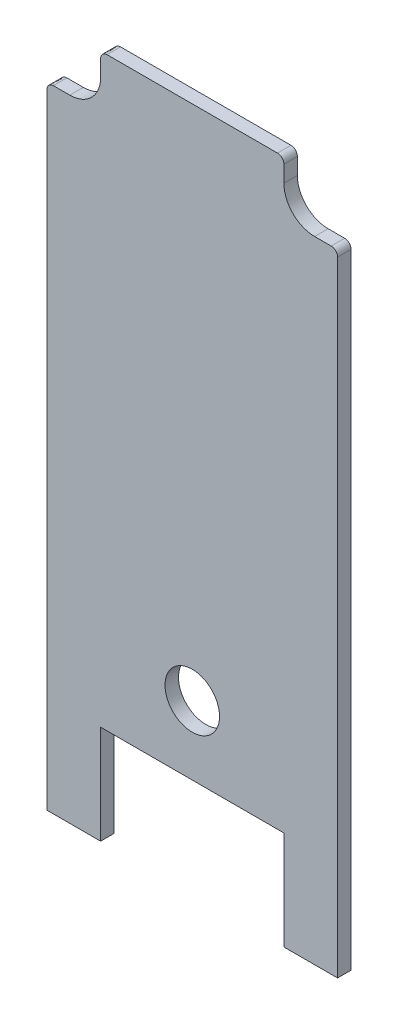
SolidWorks part; units mm, degrees
ref_plane "Front Plane" through (0, 0, 0) normal (0, 0, 1) x (1, 0, 0)
ref_plane "Top Plane" through (0, 0, 0) normal (0, 1, 0) x (1, 0, 0)
ref_plane "Right Plane" through (0, 0, 0) normal (1, 0, 0) x (0, 0, -1)
sketch3d "3DSketch1" plane through (0, 0, 0) normal (0, 0, 1) x (1, 0, 0)
  dimension "D1" = 5
sketch "Sketch2" plane through (0, 0, 5) normal (0, 0, 1) x (1, 0, 0)
  line L0 (-18.9245, -40.3) -> (-18.9245, 40.3)
  line L1 (13.25, -45.9745) -> (-13.25, -45.9745)
  line L2 (-13.25, 45.9745) -> (13.25, 45.9745)
  line L3 (18.9245, 40.3) -> (18.9245, -40.3)
  line L4 (-16.1749, 37.9745) -> (-14.25, 37.9745)
  line L5 (10.9245, 43.2249) -> (10.9245, 41.3)
  line L6 (17.1745, 36.9749) -> (17.1745, -37.0249)
  line L7 (14.25, 37.9745) -> (16.1749, 37.9745)
  line L8 (-9.9249, 44.2245) -> (9.9249, 44.2245)
  line L9 (-10.9245, 41.3) -> (-10.9245, 43.2249)
  line L10 (-17.1745, -36.9249) -> (-17.1745, 36.9749)
  line L11 (-14.25, -37.9245) -> (-16.1749, -37.9245)
  line L12 (-10.8745, -43.2249) -> (-10.8745, -41.3)
  line L13 (9.9749, -44.2245) -> (-9.8749, -44.2245)
  line L14 (10.9745, -41.3) -> (10.9745, -43.2249)
  line L15 (16.1749, -38.0245) -> (14.25, -38.0245)
  line L16 (16.1749, -38.0245) -> (14.25, -38.0245) construction
  line L17 (10.9745, -41.3) -> (10.9745, -43.2249) construction
  line L18 (9.9749, -44.2245) -> (-9.8749, -44.2245) construction
  line L19 (-10.8745, -43.2249) -> (-10.8745, -41.3) construction
  line L20 (-14.25, -37.9245) -> (-16.1749, -37.9245) construction
  line L21 (-17.1745, -36.9249) -> (-17.1745, 36.9749) construction
  line L22 (-10.9245, 41.3) -> (-10.9245, 43.2249) construction
  line L23 (-9.9249, 44.2245) -> (9.9249, 44.2245) construction
  line L24 (14.25, 37.9745) -> (16.1749, 37.9745) construction
  line L25 (17.1745, 36.9749) -> (17.1745, -37.0249) construction
  line L26 (10.9245, 43.2249) -> (10.9245, 41.3) construction
  line L27 (-16.1749, 37.9745) -> (-14.25, 37.9745) construction
  line L28 (18.9245, 40.3) -> (18.9245, -40.3) construction
  line L29 (-13.25, 45.9745) -> (13.25, 45.9745) construction
  line L30 (13.25, -45.9745) -> (-13.25, -45.9745) construction
  line L31 (-18.9245, -40.3) -> (-18.9245, 40.3) construction
  line L32 (-16.9205, -24.2245) -> (-16.9205, 36.9749)
  line L33 (-16.1749, 37.7205) -> (-14.25, 37.7205)
  line L34 (-10.6705, 41.3) -> (-10.6705, 43.2249)
  line L35 (-9.9249, 43.9705) -> (9.9249, 43.9705)
  line L36 (10.6705, 43.2249) -> (10.6705, 41.3)
  line L37 (14.25, 37.7205) -> (16.1749, 37.7205)
  line L38 (16.9205, 36.9749) -> (16.9205, -35.7245)
  line L44 (-10.6705, -24.2245) -> (10.6705, -24.2245)
  line L45 (-16.9205, -36.8196) -> (-16.9205, 36.9749) construction
  line L46 (16.9205, 36.9749) -> (16.9205, -36.9196) construction
  line L47 (17.1745, -37.0249) -> (16.1749, -38.0245) construction
  line L48 (16.9205, -36.9196) -> (16.0696, -37.7705) construction
  line L49 (10.9745, -43.2249) -> (9.9749, -44.2245) construction
  line L50 (10.7205, -43.1196) -> (9.8696, -43.9705) construction
  line L51 (-9.8749, -44.2245) -> (-10.8745, -43.2249) construction
  line L52 (-9.7696, -43.9705) -> (-10.6205, -43.1196) construction
  line L53 (-16.1749, -37.9245) -> (-17.1745, -36.9249) construction
  line L54 (-16.0696, -37.6705) -> (-16.9205, -36.8196) construction
  line L55 (0, -45.9745) -> (0, 45.9745) construction
  line L56 (-16.9205, -24.2245) -> (-10.6705, -24.2245)
  line L57 (-16.9205, -24.2245) -> (-16.9205, -35.7245)
  line L58 (-16.9205, -35.7245) -> (-10.6705, -35.7245)
  line L59 (-10.6705, -24.2245) -> (-10.6705, -35.7245)
  line L60 (16.0696, -37.7705) -> (14.25, -37.7705) construction
  line L61 (10.7205, -41.3) -> (10.7205, -43.1196) construction
  line L62 (9.8696, -43.9705) -> (-9.7696, -43.9705) construction
  line L63 (-10.6205, -43.1196) -> (-10.6205, -41.3) construction
  line L64 (-14.25, -37.6705) -> (-16.0696, -37.6705) construction
  line L65 (10.6705, -24.2245) -> (10.6705, -35.7245)
  line L66 (16.9205, -35.7245) -> (10.6705, -35.7245)
  arc A0 (-18.9245, -40.3) -> (-13.25, -45.9745) centre (-13.25, -40.3) ccw
  arc A1 (-13.25, 45.9745) -> (-18.9245, 40.3) centre (-13.25, 40.3) ccw
  arc A2 (18.9245, 40.3) -> (13.25, 45.9745) centre (13.25, 40.3) ccw
  arc A3 (13.25, -45.9745) -> (18.9245, -40.3) centre (13.25, -40.3) ccw
  arc A4 (-14.25, 37.9745) -> (-10.9245, 41.3) centre (-14.25, 41.3) ccw
  arc A5 (10.9245, 41.3) -> (14.25, 37.9745) centre (14.25, 41.3) ccw
  circle A6 centre (14.25, -41.3) radius 1.321
  circle A7 centre (-14.25, 41.3) radius 1.321
  circle A8 centre (-14.25, -41.3) radius 1.321
  circle A9 centre (14.25, 41.3) radius 1.321
  arc A10 (-10.8745, -41.3) -> (-14.25, -37.9245) centre (-14.25, -41.3) ccw
  arc A11 (14.25, -38.0245) -> (10.9745, -41.3) centre (14.25, -41.3) ccw
  arc A12 (14.25, -38.0245) -> (10.9745, -41.3) centre (14.25, -41.3) ccw construction
  arc A13 (-10.8745, -41.3) -> (-14.25, -37.9245) centre (-14.25, -41.3) ccw construction
  circle A14 centre (14.25, 41.3) radius 1.321 construction
  circle A15 centre (-14.25, -41.3) radius 1.321 construction
  circle A16 centre (-14.25, 41.3) radius 1.321 construction
  circle A17 centre (14.25, -41.3) radius 1.321 construction
  arc A18 (10.9245, 41.3) -> (14.25, 37.9745) centre (14.25, 41.3) ccw construction
  arc A19 (-14.25, 37.9745) -> (-10.9245, 41.3) centre (-14.25, 41.3) ccw construction
  arc A20 (13.25, -45.9745) -> (18.9245, -40.3) centre (13.25, -40.3) ccw construction
  arc A21 (18.9245, 40.3) -> (13.25, 45.9745) centre (13.25, 40.3) ccw construction
  arc A22 (-13.25, 45.9745) -> (-18.9245, 40.3) centre (-13.25, 40.3) ccw construction
  arc A23 (-18.9245, -40.3) -> (-13.25, -45.9745) centre (-13.25, -40.3) ccw construction
  arc A24 (-14.25, 37.7205) -> (-10.6705, 41.3) centre (-14.25, 41.3) ccw
  arc A25 (10.6705, 41.3) -> (14.25, 37.7205) centre (14.25, 41.3) ccw
  circle A28 centre (0, -16.2245) radius 3.175
  arc A40 (14.25, -37.7705) -> (10.7205, -41.3) centre (14.25, -41.3) ccw construction
  arc A41 (-10.6205, -41.3) -> (-14.25, -37.6705) centre (-14.25, -41.3) ccw construction
  spline S0 degree 3 poles (16.1749, 37.9745) (16.7605, 37.9745) (17.1745, 37.5605) (17.1745, 36.9749) knots 0 0 0 0 1 1 1 1 weights 1 0.804899 0.804899 1
  spline S1 degree 3 poles (9.9249, 44.2245) (10.5105, 44.2245) (10.9245, 43.8105) (10.9245, 43.2249) knots 0 0 0 0 1 1 1 1 weights 1 0.804899 0.804899 1
  spline S2 degree 3 poles (-10.9245, 43.2249) (-10.9245, 43.8105) (-10.5105, 44.2245) (-9.9249, 44.2245) knots 0 0 0 0 1 1 1 1 weights 1 0.804899 0.804899 1
  spline S3 degree 3 poles (-17.1745, 36.9749) (-17.1745, 37.5605) (-16.7605, 37.9745) (-16.1749, 37.9745) knots 0 0 0 0 1 1 1 1 weights 1 0.804899 0.804899 1
  spline S4 degree 3 poles (-16.1749, -37.9245) (-16.7605, -37.9245) (-17.1745, -37.5105) (-17.1745, -36.9249) knots 0 0 0 0 1 1 1 1 weights 1 0.804899 0.804899 1
  spline S5 degree 3 poles (-9.8749, -44.2245) (-10.4605, -44.2245) (-10.8745, -43.8105) (-10.8745, -43.2249) knots 0 0 0 0 1 1 1 1 weights 1 0.804899 0.804899 1
  spline S6 degree 3 poles (10.9745, -43.2249) (10.9745, -43.8105) (10.5605, -44.2245) (9.9749, -44.2245) knots 0 0 0 0 1 1 1 1 weights 1 0.804899 0.804899 1
  spline S7 degree 3 poles (17.1745, -37.0249) (17.1745, -37.6105) (16.7605, -38.0245) (16.1749, -38.0245) knots 0 0 0 0 1 1 1 1 weights 1 0.804899 0.804899 1
  spline S8 degree 3 poles (17.1745, -37.0249) (17.1745, -37.6105) (16.7605, -38.0245) (16.1749, -38.0245) knots 0 0 0 0 1 1 1 1 weights 1 0.804899 0.804899 1 construction
  spline S9 degree 3 poles (10.9745, -43.2249) (10.9745, -43.8105) (10.5605, -44.2245) (9.9749, -44.2245) knots 0 0 0 0 1 1 1 1 weights 1 0.804899 0.804899 1 construction
  spline S10 degree 3 poles (-9.8749, -44.2245) (-10.4605, -44.2245) (-10.8745, -43.8105) (-10.8745, -43.2249) knots 0 0 0 0 1 1 1 1 weights 1 0.804899 0.804899 1 construction
  spline S11 degree 3 poles (-16.1749, -37.9245) (-16.7605, -37.9245) (-17.1745, -37.5105) (-17.1745, -36.9249) knots 0 0 0 0 1 1 1 1 weights 1 0.804899 0.804899 1 construction
  spline S12 degree 3 poles (-17.1745, 36.9749) (-17.1745, 37.5605) (-16.7605, 37.9745) (-16.1749, 37.9745) knots 0 0 0 0 1 1 1 1 weights 1 0.804899 0.804899 1 construction
  spline S13 degree 3 poles (-10.9245, 43.2249) (-10.9245, 43.8105) (-10.5105, 44.2245) (-9.9249, 44.2245) knots 0 0 0 0 1 1 1 1 weights 1 0.804899 0.804899 1 construction
  spline S14 degree 3 poles (9.9249, 44.2245) (10.5105, 44.2245) (10.9245, 43.8105) (10.9245, 43.2249) knots 0 0 0 0 1 1 1 1 weights 1 0.804899 0.804899 1 construction
  spline S15 degree 3 poles (16.1749, 37.9745) (16.7605, 37.9745) (17.1745, 37.5605) (17.1745, 36.9749) knots 0 0 0 0 1 1 1 1 weights 1 0.804899 0.804899 1 construction
  spline S16 degree 1 poles (-16.9205, 36.9749) (-16.1749, 37.7205) knots 0 0 1 1 construction
  spline S17 degree 1 poles (-10.6705, 43.2249) (-9.9249, 43.9705) knots 0 0 1 1 construction
  spline S18 degree 1 poles (9.9249, 43.9705) (10.6705, 43.2249) knots 0 0 1 1 construction
  spline S19 degree 1 poles (16.1749, 37.7205) (16.9205, 36.9749) knots 0 0 1 1 construction
  spline S24 degree 3 poles (-16.9205, 36.9749) (-16.9205, 37.068) (-16.8885, 37.2502) (-16.7186, 37.5186) (-16.4502, 37.6885) (-16.268, 37.7205) (-16.1749, 37.7205) knots 0 0 0 0 0.25 0.5 0.75 1 1 1 1
  spline S25 degree 3 poles (-10.6705, 43.2249) (-10.6705, 43.318) (-10.6385, 43.5002) (-10.4686, 43.7686) (-10.2002, 43.9385) (-10.018, 43.9705) (-9.9249, 43.9705) knots 0 0 0 0 0.25 0.5 0.75 1 1 1 1
  spline S26 degree 3 poles (9.9249, 43.9705) (10.018, 43.9705) (10.2002, 43.9385) (10.4686, 43.7686) (10.6385, 43.5002) (10.6705, 43.318) (10.6705, 43.2249) knots 0 0 0 0 0.25 0.5 0.75 1 1 1 1
  spline S27 degree 3 poles (16.1749, 37.7205) (16.268, 37.7205) (16.4502, 37.6885) (16.7186, 37.5186) (16.8885, 37.2502) (16.9205, 37.068) (16.9205, 36.9749) knots 0 0 0 0 0.25 0.5 0.75 1 1 1 1
  dimension "D5" = 6.35
  dimension "D2" = 20
  dimension "D3" = 11.5
  dimension "D4" = 6.25
  dimension "D6" = 8
  dimension "D1" = 0.254
extrude "Boss-Extrude1" add sketch "Sketch2" along normal blind 1.57 contours S27 L37 A25 L36 S26 L35 S25 L34 A24 L33 S24 L32 L44 L38 A28 | L57 L56 L59 L58
